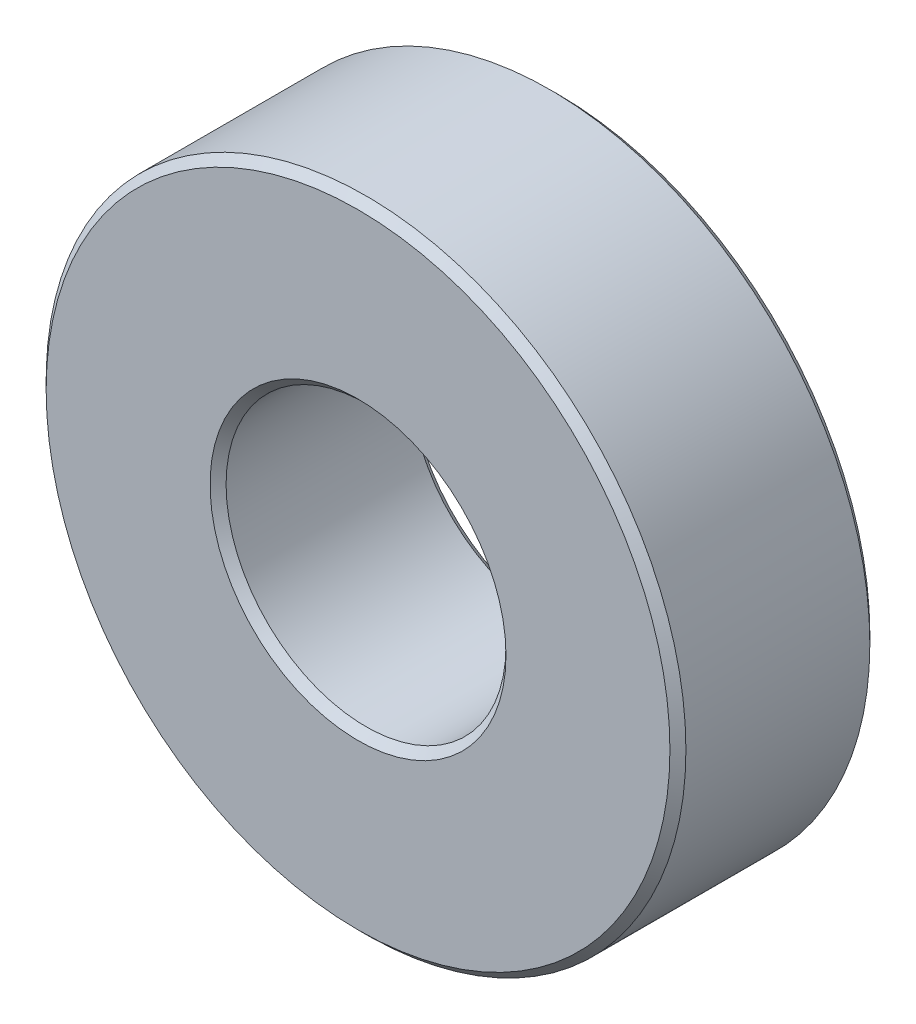
SolidWorks part; units mm, degrees
ref_plane "Plan1" through (0, 0, 0) normal (0, 0, 1) x (1, 0, 0)
ref_plane "Plan2" through (0, 0, 0) normal (0, 1, 0) x (1, 0, 0)
ref_plane "Plan3" through (0, 0, 0) normal (1, 0, 0) x (0, 0, -1)
sketch "Esquisse1" plane through (0, 0, 0) normal (0, 0, 1) x (1, 0, 0)
  circle A0 centre (0, 0) radius 3.5
  circle A1 centre (0, 0) radius 8
  dimension "D1" = 16
  dimension "D2" = 7
extrude "Base-Extrusion" add sketch "Esquisse1" along normal blind 5
chamfer "Chanfrein1" distance 0.2 angle 45
